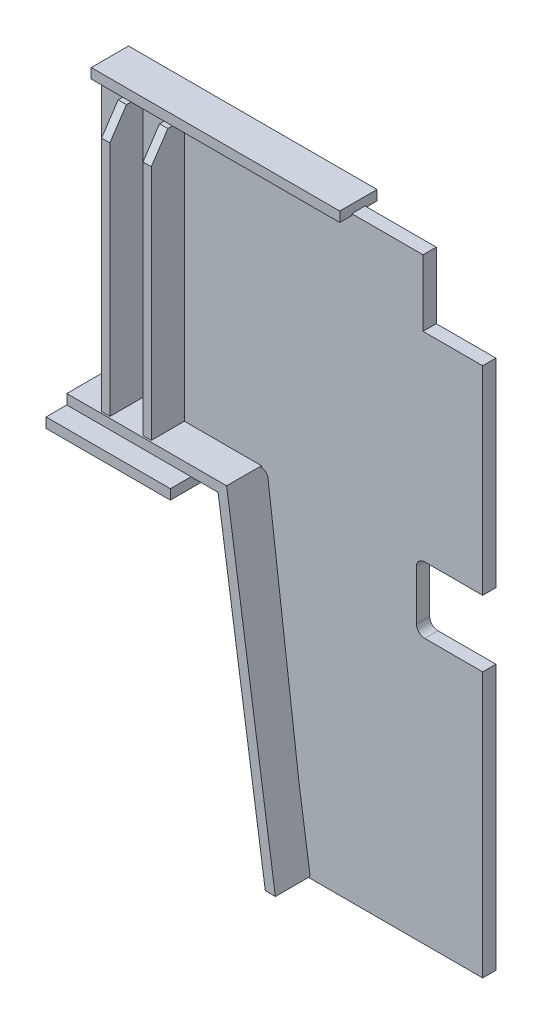
SolidWorks part; units mm, degrees
ref_plane "前视" through (0, 0, 0) normal (0, 0, 1) x (1, 0, 0)
ref_plane "上视" through (0, 0, 0) normal (0, 1, 0) x (1, 0, 0)
ref_plane "右视" through (0, 0, 0) normal (1, 0, 0) x (0, 0, -1)
sketch "草图1" plane through (0, 0, 0) normal (0, 0, 1) x (1, 0, 0)
  line L0 (0, -320) -> (-70, -320)
  line L1 (-72, 0) -> (-460, 0)
  line L2 (-40, 116.6722) -> (-40, -759.2574) construction
  line L3 (0, -720) -> (-210, -720)
  line L4 (-460, 0) -> (-460, -320)
  line L5 (-80, -330) -> (-80, -390)
  line L6 (-70, -400) -> (0, -400)
  line L7 (0, -400) -> (0, -720)
  line L8 (-112, 271.0914) -> (-112, -671.0914) construction
  line L9 (-775.8996, -110) -> (-214.577, -110) construction
  line L15 (-210, -720) -> (-259.124, -327.0077)
  line L16 (-460, -320) -> (-267.0623, -320)
  line L17 (-72, 0) -> (-72, -80)
  line L18 (-72, -80) -> (0, -80)
  line L19 (0, -80) -> (0, -320)
  arc A0 (-80, -330) -> (-70, -320) centre (-70, -330) cw
  arc A1 (-70, -400) -> (-80, -390) centre (-70, -390) cw
  arc A11 (-259.124, -327.0077) -> (-267.0623, -320) centre (-267.0623, -328) ccw
  point P11 (-80, -320)
  point P49 (-260, -320)
  dimension "D4" = 10
  dimension "D5" = 10
  dimension "D13" = 72
  dimension "D14" = 80
  dimension "D18" = 72
  dimension "D20" = 80
  dimension "D24" = 8
  dimension "D6" = 720
  dimension "D7" = 72
  dimension "D8" = 320
  dimension "D9" = 320
  dimension "D10" = 460
  dimension "D11" = 80
  dimension "D12" = 40
  dimension "D21" = 210
  dimension "D22" = 392.9923
  dimension "D33" = 110
extrude "基体-拉伸" add sketch "草图1" along normal blind 16
sketch "草图3" plane through (0, 0, 16) normal (0, 0, 1) x (1, 0, 0)
  line L1 (-420, -2) -> (-410, -2)
  line L2 (-420, -2) -> (-420, -318)
  line L3 (-420, -318) -> (-410, -318)
  line L4 (-410, -2) -> (-410, -318)
  line L7 (-370, -2) -> (-360, -2)
  line L8 (-370, -2) -> (-370, -318)
  line L9 (-370, -318) -> (-360, -318)
  line L10 (-360, -2) -> (-360, -318)
  dimension "D1" = 10
  dimension "D2" = 10
  dimension "D4" = 40
extrude "凸台-拉伸2" add sketch "草图3" along normal blind 40 and the other way blind 56
sketch "草图4" plane through (-420, 0, 0) normal (-1, 0, 0) x (0, 0, 1)
  line L0 (-20, -2) -> (-45.5, -32)
  line L1 (0, -2) -> (-40, -2) construction
  line L3 (-20, -2) -> (-45.5, -2)
  line L4 (-45.5, -2) -> (-45.5, -32)
  dimension "D1" = 30
  dimension "D2" = 25.5
extrude "切除-拉伸1" cut sketch "草图4" against normal through all
sketch "草图5" plane through (-420, 0, 0) normal (-1, 0, 0) x (0, 0, 1)
  line L0 (36, -2) -> (56, -32)
  line L1 (56, -2) -> (16, -2) construction
  line L2 (56, -2) -> (56, -318) construction
  line L3 (36, -2) -> (56, -2)
  line L4 (56, -2) -> (56, -32)
  dimension "D1" = 30
extrude "切除-拉伸2" cut sketch "草图5" against normal through all
sketch "草图6" plane through (0, 0, 16) normal (0, 0, 1) x (1, 0, 0)
  line L1 (-267.0623, -318) -> (-460, -318)
  line L2 (-267.0623, -318) -> (-208.2344, -718)
  line L3 (-277.4265, -330) -> (-460, -330)
  line L4 (-460, -318) -> (-460, -330)
  line L6 (-277.4265, -330) -> (-220.3635, -718)
  line L7 (-220.3635, -718) -> (-208.2344, -718)
  dimension "D1" = 12
  dimension "D2" = 12
extrude "凸台-拉伸5" add sketch "草图6" along normal blind 42 and the other way blind 58
sketch "草图7" plane through (0, 0, 0) normal (0, 0, -1) x (-1, 0, 0)
  line L1 (458, -2) -> (158, -2)
  line L2 (458, -2) -> (458, 10)
  line L3 (458, 10) -> (158, 10)
  line L4 (158, -2) -> (158, 10)
  dimension "D1" = 300
  dimension "D2" = 12
extrude "凸台-拉伸6" add sketch "草图7" along normal blind 14.5 and the other way blind 30.5
sketch "草图8" plane through (0, -330, 0) normal (0, -1, 0) x (1, 0, 0)
  line L0 (-515.842, 8) -> (-234.809, 8) construction
  line L1 (-460, -42) -> (-277.4265, -42) construction
  line L2 (-460, 58) -> (-277.4265, 58) construction
  line L4 (-310, 83) -> (-460, 83)
  line L5 (-310, 83) -> (-310, -67)
  line L6 (-310, -67) -> (-460, -67)
  line L7 (-460, 83) -> (-460, -67)
  line L8 (-460, 58) -> (-460, -42) construction
  dimension "D1" = 150
  dimension "D2" = 150
extrude "凸台-拉伸7" add sketch "草图8" along normal blind 12
